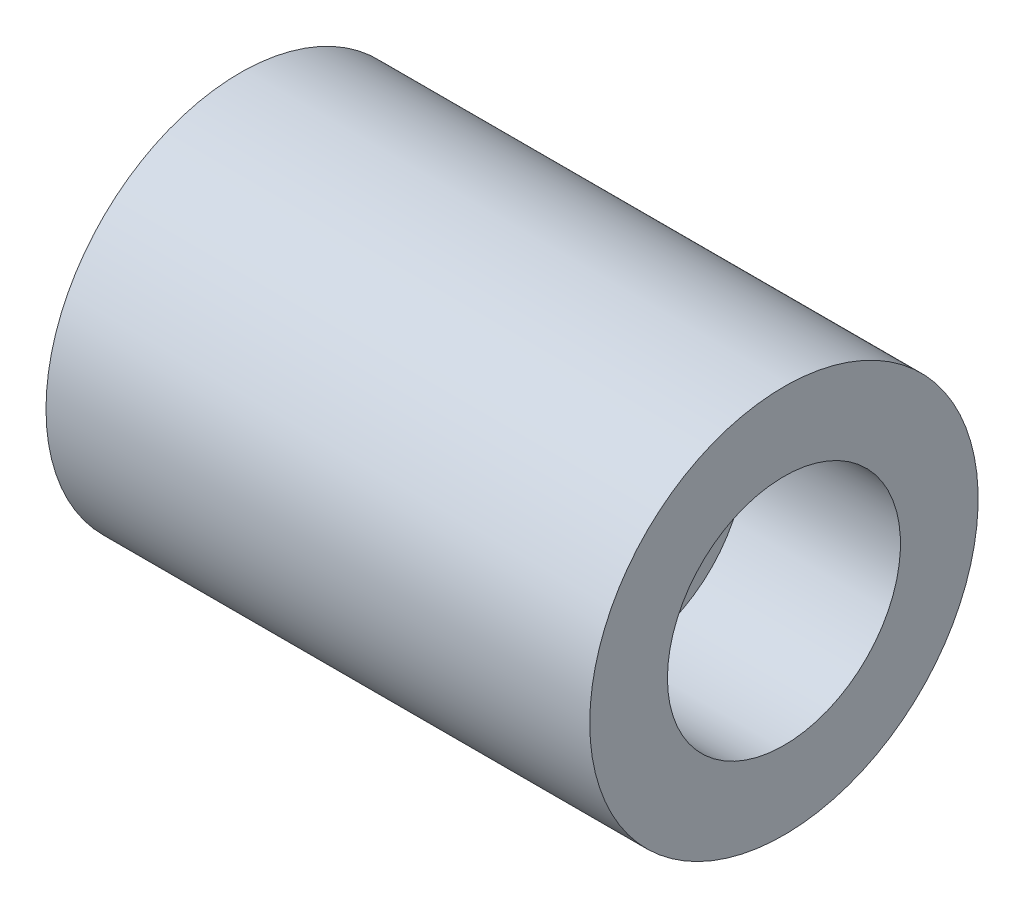
SolidWorks part; units mm, degrees
ref_plane "前基準面" through (0, 0, 0) normal (0, 0, 1) x (1, 0, 0)
ref_plane "上基準面" through (0, 0, 0) normal (0, 1, 0) x (1, 0, 0)
ref_plane "右基準面" through (0, 0, 0) normal (1, 0, 0) x (0, 0, -1)
sketch "草圖1" plane through (0, 0, 0) normal (0, 0, 1) x (1, 0, 0)
  line L1 (0, 0) -> (20, 0)
  line L2 (0, 0) -> (0, 50)
  line L3 (0, 50) -> (20, 50)
  line L4 (20, 0) -> (20, 50)
  line L5 (20, 50) -> (100, 50)
  line L6 (20, 50) -> (20, 10)
  line L7 (20, 10) -> (100, 10)
  line L8 (100, 50) -> (100, 10)
  line L9 (100, 50) -> (140, 50)
  line L10 (100, 50) -> (100, 30)
  line L11 (100, 30) -> (140, 30)
  line L12 (140, 50) -> (140, 30)
  dimension "D1" = 140
  dimension "D2" = 120
  dimension "D3" = 40
  dimension "D4" = 50
  dimension "D5" = 10
  dimension "D6" = 20
revolve "旋轉1" add sketch "草圖1" angle 360 about L1
